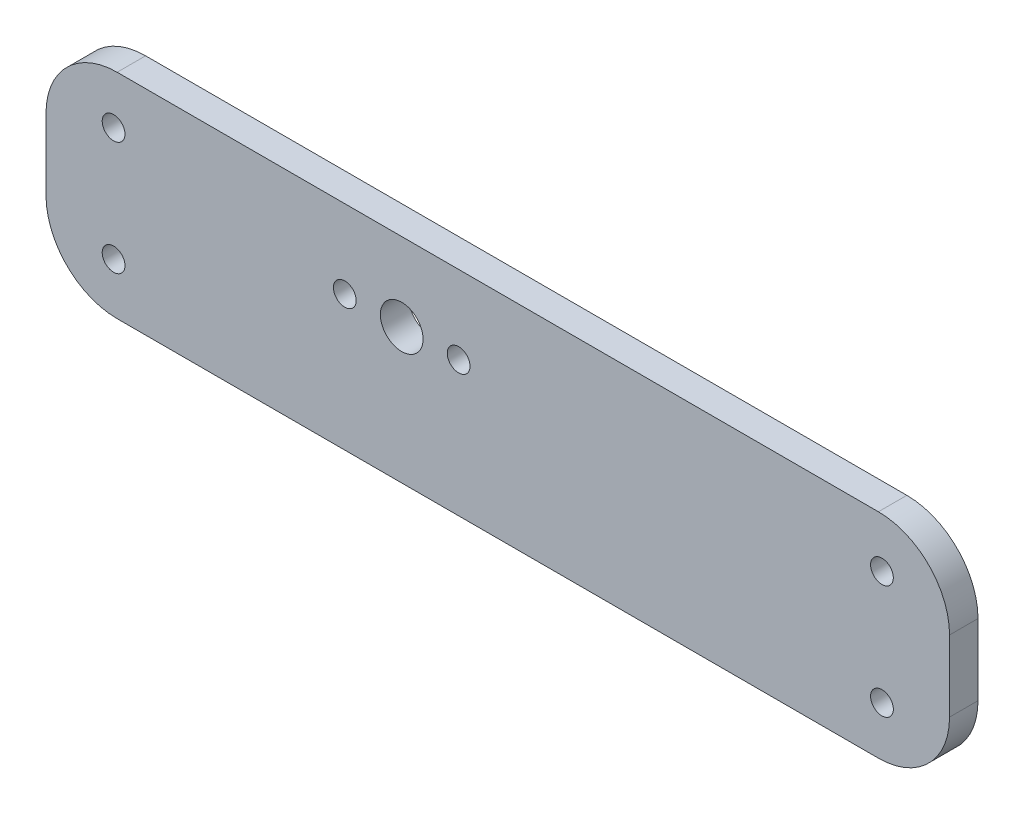
SolidWorks part; units mm, degrees
material "MDF"
ref_plane "Plano frontal" through (0, 0, 0) normal (0, 0, 1) x (1, 0, 0)
ref_plane "Plano superior" through (0, 0, 0) normal (0, 1, 0) x (1, 0, 0)
ref_plane "Plano direito" through (0, 0, 0) normal (1, 0, 0) x (0, 0, -1)
sketch "Esboço1" plane through (0, 0, 0) normal (0, 0, 1) x (1, 0, 0)
  line L0 (-21.5, 4) -> (-5.5, 4) construction
  line L1 (-63.5, -15) -> (63.5, -15)
  line L2 (-63.5, -15) -> (-63.5, 15)
  line L3 (-63.5, 15) -> (63.5, 15)
  line L4 (63.5, -15) -> (63.5, 15)
  line L5 (0, 15) -> (0, -15) construction
  line L6 (-63.5, 0) -> (63.5, 0) construction
  line L7 (44.5, 15) -> (44.5, -15) construction
  line L8 (-44.5, 15) -> (-44.5, -15) construction
  line L9 (-44.5, 5.3275) -> (-63.5, 5.3275) construction
  circle A0 centre (-13.5, 4) radius 3
  circle A1 centre (-5.5, 4) radius 1.6
  circle A2 centre (-21.5, 4) radius 1.6
  circle A4 centre (-54, 8) radius 1.6
  circle A5 centre (-54, -8) radius 1.6
  circle A6 centre (54, -8) radius 1.6
  circle A7 centre (54, 8) radius 1.6
  point P0 (0, 0)
  point P21 (-54, 5.3275)
  dimension "D1" = 3.2
  dimension "D2" = 6
  dimension "D4" = 31
  dimension "D9" = 16
  dimension "D3" = 16
  dimension "D5" = 11
  dimension "D6" = 19
  dimension "D7" = 58
  dimension "D8" = 30
extrude "Ressalto-extrusão1" add sketch "Esboço1" along normal blind 4
fillet "Filete1" radius 10 4 edges at (-63.5, 15, 2) (-63.5, -15, 2) (63.5, -15, 2) (63.5, 15, 2)
